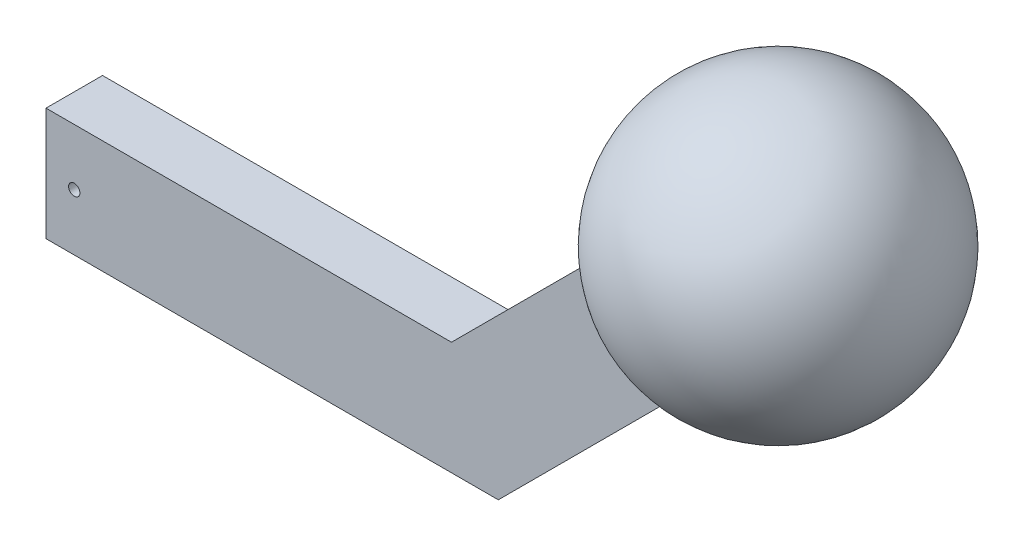
SolidWorks part; units mm, degrees
ref_plane "Front Plane" through (0, 0, 0) normal (0, 0, 1) x (1, 0, 0)
ref_plane "Top Plane" through (0, 0, 0) normal (0, 1, 0) x (1, 0, 0)
ref_plane "Right Plane" through (0, 0, 0) normal (1, 0, 0) x (0, 0, -1)
sketch "Sketch1" plane through (0, 0, 0) normal (0, 0, 1) x (1, 0, 0)
  line L0 (0, 0) -> (80, 0)
  line L1 (80, 0) -> (115.3553, 35.3553)
  line L2 (115.3553, 35.3553) -> (101.2132, 49.4975)
  line L3 (101.2132, 49.4975) -> (71.7157, 20)
  line L4 (71.7157, 20) -> (0, 20)
  line L5 (0, 20) -> (0, 0)
  circle A1 centre (5, 10) radius 1
  point P9 (103.7868, 25)
  point P10 (103.7868, 25)
  dimension "D6" = 10
  dimension "D7" = 5
  dimension "D8" = 2
  dimension "D1" = 20
  dimension "D2" = 20
  dimension "D3" = 135
  dimension "D4" = 80
  dimension "D5" = 50
extrude "Boss-Extrude1" add sketch "Sketch1" along normal blind 10
ref_plane "Plane1" through (0, 0, 5) normal (0, 0, 1) x (1, 0, 0)
sketch "Sketch2" plane through (0, 0, 5) normal (0, 0, 1) x (1, 0, 0)
  line L0 (115.3553, 35.3553) -> (101.2132, 49.4975) construction
  line L1 (115.3553, 35.3553) -> (108.2843, 42.4264) construction
  line L2 (108.2843, 42.4264) -> (142.1638, 76.3059)
  line L3 (108.2843, 42.4264) -> (115.3553, 35.3553)
  line L4 (115.3553, 35.3553) -> (101.2132, 49.4975) construction
  arc A0 (142.1638, 76.3059) -> (115.3553, 35.3553) centre (124.4861, 58.6283) cw
  point P0 (108.2843, 42.4264)
  point P2 (111.8198, 38.8909)
  dimension "D1" = 25
revolve "Revolve2" add sketch "Sketch2" angle 360 about L2
sketch "Sketch4" plane through (0, 0, 0) normal (0, 0, -1) x (-1, 0, 0)
  line L0 (0, 20) -> (0, 0) construction
  line L1 (0, 13.5) -> (-23, 13.5)
  line L2 (0, 13.5) -> (0, 6.5)
  line L3 (0, 6.5) -> (-23, 6.5)
  line L4 (-23, 13.5) -> (-23, 6.5)
  circle A0 centre (-5, 10) radius 1 construction
  dimension "D1" = 7
  dimension "D2" = 3.5
  dimension "D3" = 23
extrude "Cut-Extrude2" cut sketch "Sketch4" against normal blind 2
